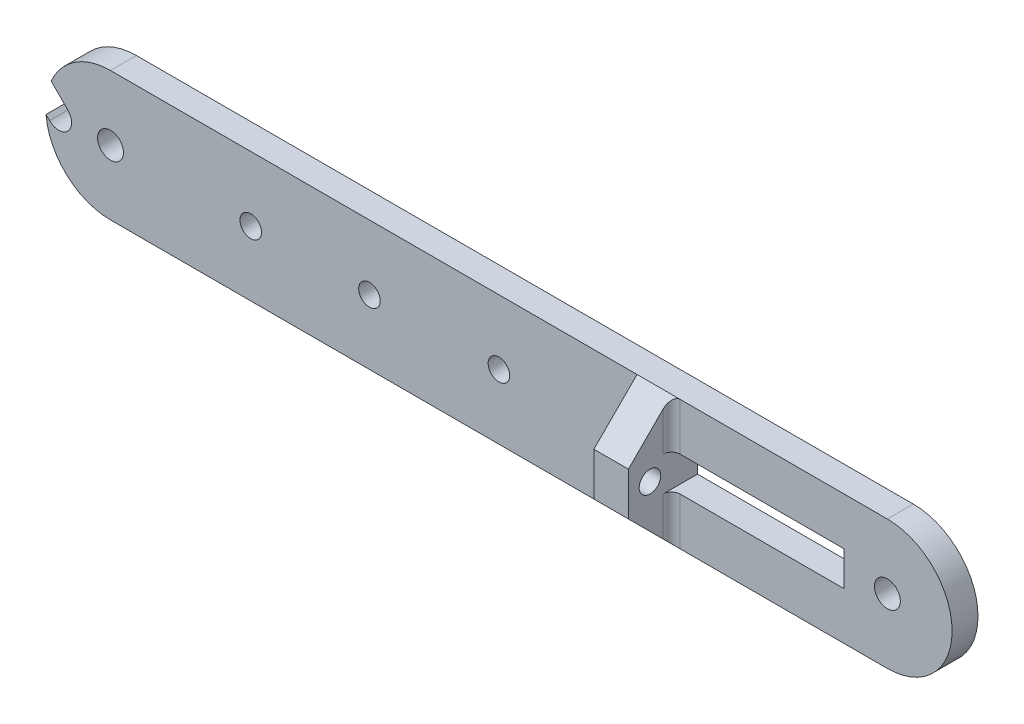
SolidWorks part; units mm, degrees
ref_plane "Plan de face" through (0, 0, 0) normal (0, 0, 1) x (1, 0, 0)
ref_plane "Plan de dessus" through (0, 0, 0) normal (0, 1, 0) x (1, 0, 0)
ref_plane "Plan de droite" through (0, 0, 0) normal (1, 0, 0) x (0, 0, -1)
sketch "Esquisse1" plane through (0, 0, 0) normal (0, 0, 1) x (1, 0, 0)
  line L0 (-74.3787, 0) -> (69.7437, 0) construction
  line L1 (0, 0) -> (0, 19.0596) construction
  line L2 (90, -15) -> (-90, -15)
  line L3 (90, 15) -> (-90, 15)
  line L5 (40, -4) -> (80, -4)
  line L6 (40, -4) -> (40, 4)
  line L7 (40, 4) -> (80, 4)
  line L8 (80, -4) -> (80, 4)
  line L9 (40, -4) -> (80, 4) construction
  line L10 (40, 4) -> (80, -4) construction
  arc A0 (90, -15) -> (90, 15) centre (90, 0) ccw
  circle A1 centre (90, 0) radius 3
  circle A2 centre (-90, 0) radius 3
  arc A3 (-90, -15) -> (-90, 15) centre (-90, 0) cw
  circle A4 centre (0, 0) radius 2.5
  circle A5 centre (-57.5, 0) radius 2.5
  circle A6 centre (-30, 0) radius 2.5
  point P4 (60, 0)
  point P17 (0, -15)
  point P20 (0, 15)
  dimension "D1" = 30
  dimension "D3" = 6
  dimension "D7" = 5
  dimension "D8" = 5
  dimension "D9" = 5
  dimension "D2" = 90
  dimension "D4" = 8
  dimension "D5" = 40
  dimension "D6" = 60
  dimension "D10" = 30
  dimension "D11" = 30
extrude "Boss.-Extru.1" add sketch "Esquisse1" along normal blind 6
sketch "Esquisse2" plane through (40, 0, 0) normal (1, 0, 0) x (0, 0, -1)
  line L0 (0, -4) -> (-6, 4) construction
  line L1 (-6, 4) -> (-6, 0) construction
  line L2 (-6, 4) -> (-6, -4) construction
  line L3 (-6, 0) -> (-15.5036, 0) construction
  line L4 (-6, 15) -> (-6, -15) construction
  line L6 (-16, 5) -> (-16, -5)
  line L8 (-6, 5) -> (-6, -5)
  line L9 (-16, 5) -> (-6, -5) construction
  line L10 (-16, -5) -> (-6, 5) construction
  line L11 (-6, -15) -> (-16, -5)
  line L12 (-6, -15) -> (-6, -5)
  line L13 (-6, 5) -> (-6, 15)
  line L14 (-6, 15) -> (-16, 5)
  circle A0 centre (-11, 0) radius 2.5
  point P7 (-11, 0)
  dimension "D3" = 5
  dimension "D1" = 10
  dimension "D2" = 10
extrude "Boss.-Extru.2" add sketch "Esquisse2" against normal blind 8
fillet "Congé2" radius 2 2 edges
sketch "Esquisse3" plane through (32, 0, 0) normal (-1, 0, 0) x (0, 0, 1)
  line L0 (11, 0) -> (11, 4) construction
  line L1 (11, 0) -> (14.4641, 2) construction
  line L2 (11, 0) -> (14.4641, -2) construction
  line L3 (11, 4) -> (14.4641, 2)
  line L4 (14.4641, 2) -> (14.4641, -2)
  line L5 (14.4641, -2) -> (11, -4)
  line L6 (7.5359, 2) -> (7.5359, -2)
  line L7 (11, 4) -> (7.5359, 2)
  line L8 (7.5359, -2) -> (11, -4)
  dimension "D2" = 60
  dimension "D3" = 60
extrude "Enlèv. mat.-Extru.1" cut sketch "Esquisse3" against normal blind 4
sketch "Esquisse4" plane through (0, 0, 6) normal (0, 0, 1) x (1, 0, 0)
  line L0 (-90, 0) -> (-105, 0) construction
  line L1 (-105, 0) -> (-102, 0) construction
  line L2 (-102, 0) -> (-104.1213, -2.1213) construction
  line L3 (-104.1213, -2.1213) -> (-99.8787, 2.1213)
  line L4 (-104.1213, -2.1213) -> (-99.8787, 2.1213)
  line L5 (-104.1213, -2.1213) -> (-108.504, 2.2614)
  line L6 (-99.8787, 2.1213) -> (-104.2614, 6.504)
  line L7 (-108.504, 2.2614) -> (-104.2614, 6.504)
  arc A0 (-90, 15) -> (-90, -15) centre (-90, 0) ccw construction
  circle A1 centre (-102, 0) radius 3
  arc M9 (-90, 15) -> (-90, -15) centre (-90, 0) ccw
  dimension "D1" = 3
  dimension "D2" = 45
extrude "Enlèv. mat.-Extru.4" cut sketch "Esquisse4" against normal blind 10 contours L3 A1 | A1 L6 M9 | A1 L5 M9 | L3 A1
